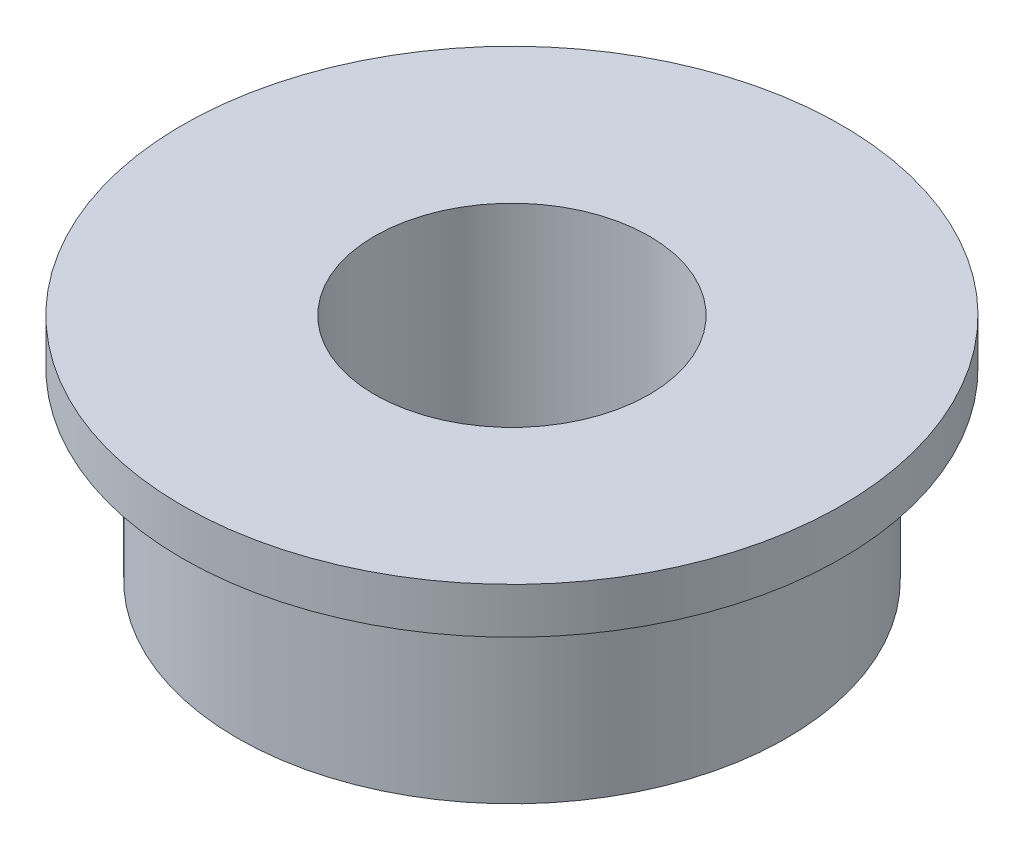
SolidWorks part; units mm, degrees
ref_plane "前视基准面" through (0, 0, 0) normal (0, 0, 1) x (1, 0, 0)
ref_plane "上视基准面" through (0, 0, 0) normal (0, 1, 0) x (1, 0, 0)
ref_plane "右视基准面" through (0, 0, 0) normal (1, 0, 0) x (0, 0, -1)
sketch "草图1" plane through (0, 0, 0) normal (0, 1, 0) x (1, 0, 0)
  circle A0 centre (0, 0) radius 1.5
  circle A1 centre (0, 0) radius 3
  dimension "D1" = 3
  dimension "D2" = 6
extrude "凸台-拉伸1" add sketch "草图1" along normal blind 2
sketch "草图2" plane through (0, 2, 0) normal (0, 1, 0) x (1, 0, 0)
  circle A0 centre (0, 0) radius 3.6
  circle A1 centre (0, 0) radius 1.5
  dimension "D1" = 7.2
extrude "凸台-拉伸2" add sketch "草图2" along normal blind 0.5
